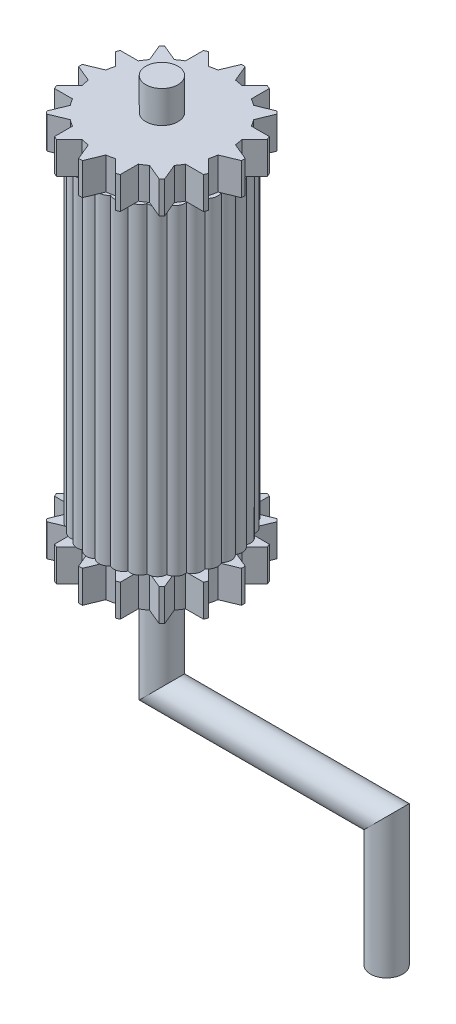
SolidWorks part; units mm, degrees
ref_plane "Front Plane" through (0, 0, 0) normal (1, 0, 0) x (0, 1, 0)
ref_plane "Top Plane" through (0, 0, 0) normal (0, 0, 1) x (0, 1, 0)
ref_plane "Right Plane" through (0, 0, 0) normal (0, 1, 0) x (-1, 0, 0)
sketch "Sketch2" plane through (0, 0, 0) normal (0, 1, 0) x (-1, 0, 0)
  arc A83 (20.6915, 2.1748) -> (20.6915, -2.1748) centre (18.625, 0) cw
  arc A84 (20.6915, -2.1748) -> (19.7872, -6.4292) centre (18.218, -3.8724) cw
  arc A85 (19.7872, -6.4292) -> (18.0181, -10.4027) centre (17.0148, -7.5755) cw
  arc A86 (18.0181, -10.4027) -> (15.4615, -13.9216) centre (15.0679, -10.9475) cw
  arc A87 (15.4615, -13.9216) -> (12.2291, -16.832) centre (12.4626, -13.8411) cw
  arc A88 (12.2291, -16.832) -> (8.4623, -19.0067) centre (9.3125, -16.1297) cw
  arc A89 (8.4623, -19.0067) -> (4.3257, -20.3508) centre (5.7554, -17.7134) cw
  arc A90 (4.3257, -20.3508) -> (0, -20.8055) centre (1.9468, -18.523) cw
  arc A91 (0, -20.8055) -> (-4.3257, -20.3508) centre (-1.9468, -18.523) cw
  arc A92 (-4.3257, -20.3508) -> (-8.4623, -19.0067) centre (-5.7554, -17.7134) cw
  arc A93 (-8.4623, -19.0067) -> (-12.2291, -16.832) centre (-9.3125, -16.1297) cw
  arc A94 (-12.2291, -16.832) -> (-15.4615, -13.9216) centre (-12.4626, -13.8411) cw
  arc A95 (-15.4615, -13.9216) -> (-18.0181, -10.4027) centre (-15.0679, -10.9475) cw
  arc A96 (-18.0181, -10.4027) -> (-19.7872, -6.4292) centre (-17.0148, -7.5755) cw
  arc A97 (-19.7872, -6.4292) -> (-20.6915, -2.1748) centre (-18.218, -3.8724) cw
  arc A98 (-20.6915, -2.1748) -> (-20.6915, 2.1748) centre (-18.625, 0) cw
  arc A99 (-20.6915, 2.1748) -> (-19.7872, 6.4292) centre (-18.218, 3.8724) cw
  arc A100 (-19.7872, 6.4292) -> (-18.0181, 10.4027) centre (-17.0148, 7.5755) cw
  arc A101 (-18.0181, 10.4027) -> (-15.4615, 13.9216) centre (-15.0679, 10.9475) cw
  arc A102 (-15.4615, 13.9216) -> (-12.2291, 16.832) centre (-12.4626, 13.8411) cw
  arc A103 (-12.2291, 16.832) -> (-8.4623, 19.0067) centre (-9.3125, 16.1297) cw
  arc A104 (-8.4623, 19.0067) -> (-4.3257, 20.3508) centre (-5.7554, 17.7134) cw
  arc A105 (-4.3257, 20.3508) -> (0, 20.8055) centre (-1.9468, 18.523) cw
  arc A106 (0, 20.8055) -> (4.3257, 20.3508) centre (1.9468, 18.523) cw
  arc A107 (4.3257, 20.3508) -> (8.4623, 19.0067) centre (5.7554, 17.7134) cw
  arc A108 (8.4623, 19.0067) -> (12.2291, 16.832) centre (9.3125, 16.1297) cw
  arc A109 (12.2291, 16.832) -> (15.4615, 13.9216) centre (12.4626, 13.8411) cw
  arc A110 (15.4615, 13.9216) -> (18.0181, 10.4027) centre (15.0679, 10.9475) cw
  arc A111 (18.0181, 10.4027) -> (19.7872, 6.4292) centre (17.0148, 7.5755) cw
  arc A112 (19.7872, 6.4292) -> (20.6915, 2.1748) centre (18.218, 3.8724) cw
  point P0 (0, 0)
  point P31 (0, 0)
  point P62 (0, 0)
  dimension "D1" = 3
extrude "Boss-Extrude2" add sketch "Sketch2" along normal blind 100
sketch "Sketch3" plane through (0, 0, 0) normal (0, -1, 0) x (1, 0, 0)
  line L0 (0, -57.0817) -> (0, 57.0817) construction
  line L1 (0, 25.375) -> (2.1167, 20.2647) construction
  line L2 (0, 25.375) -> (-2.1167, 20.2647) construction
  line L5 (-2.733, 20.1909) -> (2.733, 20.1909) construction
  line L32 (-2.733, 20.1909) -> (-0.5885, 25.3682)
  line L33 (2.733, 20.1909) -> (0.5885, 25.3682)
  line L34 (5.2017, 19.6998) -> (9.1643, 23.6623)
  line L35 (10.2517, 17.6081) -> (10.2517, 23.2119)
  line L36 (12.3446, 16.2096) -> (17.5219, 18.3541)
  line L37 (16.2096, 12.3446) -> (18.3541, 17.5219)
  line L38 (17.6081, 10.2517) -> (23.2119, 10.2517)
  line L39 (19.6998, 5.2017) -> (23.6623, 9.1643)
  line L40 (20.1909, 2.733) -> (25.3682, 0.5885)
  line L41 (20.1909, -2.733) -> (25.3682, -0.5885)
  line L42 (19.6998, -5.2017) -> (23.6623, -9.1643)
  line L43 (17.6081, -10.2517) -> (23.2119, -10.2517)
  line L44 (16.2096, -12.3446) -> (18.3541, -17.5219)
  line L45 (12.3446, -16.2096) -> (17.5219, -18.3541)
  line L46 (10.2517, -17.6081) -> (10.2517, -23.2119)
  line L47 (5.2017, -19.6998) -> (9.1643, -23.6623)
  line L48 (2.733, -20.1909) -> (0.5885, -25.3682)
  line L49 (-2.733, -20.1909) -> (-0.5885, -25.3682)
  line L50 (-5.2017, -19.6998) -> (-9.1643, -23.6623)
  line L51 (-10.2517, -17.6081) -> (-10.2517, -23.2119)
  line L52 (-12.3446, -16.2096) -> (-17.5219, -18.3541)
  line L53 (-16.2096, -12.3446) -> (-18.3541, -17.5219)
  line L54 (-17.6081, -10.2517) -> (-23.2119, -10.2517)
  line L55 (-19.6998, -5.2017) -> (-23.6623, -9.1643)
  line L56 (-20.1909, -2.733) -> (-25.3682, -0.5885)
  line L57 (-20.1909, 2.733) -> (-25.3682, 0.5885)
  line L58 (-19.6998, 5.2017) -> (-23.6623, 9.1643)
  line L59 (-17.6081, 10.2517) -> (-23.2119, 10.2517)
  line L60 (-16.2096, 12.3446) -> (-18.3541, 17.5219)
  line L61 (-12.3446, 16.2096) -> (-17.5219, 18.3541)
  line L62 (-10.2517, 17.6081) -> (-10.2517, 23.2119)
  line L63 (-5.2017, 19.6998) -> (-9.1643, 23.6623)
  arc A28 (-16.2096, 12.3446) -> (-17.6081, 10.2517) centre (0, 0) ccw
  arc A29 (-23.2119, 10.2517) -> (-23.6623, 9.1643) centre (0, 0) ccw
  arc A30 (-17.5219, 18.3541) -> (-18.3541, 17.5219) centre (0, 0) ccw
  arc A31 (-10.2517, 17.6081) -> (-12.3446, 16.2096) centre (0, 0) ccw
  arc A32 (-9.1643, 23.6623) -> (-10.2517, 23.2119) centre (0, 0) ccw
  arc A33 (0.5885, 25.3682) -> (-0.5885, 25.3682) centre (0, 0) ccw
  arc A34 (10.2517, 23.2119) -> (9.1643, 23.6623) centre (0, 0) ccw
  arc A35 (-2.733, 20.1909) -> (-5.2017, 19.6998) centre (0, 0) ccw
  arc A36 (5.2017, 19.6998) -> (2.733, 20.1909) centre (0, 0) ccw
  arc A37 (18.3541, 17.5219) -> (17.5219, 18.3541) centre (0, 0) ccw
  arc A38 (12.3446, 16.2096) -> (10.2517, 17.6081) centre (0, 0) ccw
  arc A39 (17.6081, 10.2517) -> (16.2096, 12.3446) centre (0, 0) ccw
  arc A40 (23.6623, 9.1643) -> (23.2119, 10.2517) centre (0, 0) ccw
  arc A41 (25.3682, -0.5885) -> (25.3682, 0.5885) centre (0, 0) ccw
  arc A42 (23.2119, -10.2517) -> (23.6623, -9.1643) centre (0, 0) ccw
  arc A43 (20.1909, 2.733) -> (19.6998, 5.2017) centre (0, 0) ccw
  arc A44 (19.6998, -5.2017) -> (20.1909, -2.733) centre (0, 0) ccw
  arc A45 (17.5219, -18.3541) -> (18.3541, -17.5219) centre (0, 0) ccw
  arc A46 (9.1643, -23.6623) -> (10.2517, -23.2119) centre (0, 0) ccw
  arc A47 (10.2517, -17.6081) -> (12.3446, -16.2096) centre (0, 0) ccw
  arc A48 (16.2096, -12.3446) -> (17.6081, -10.2517) centre (0, 0) ccw
  arc A49 (-0.5885, -25.3682) -> (0.5885, -25.3682) centre (0, 0) ccw
  arc A50 (-10.2517, -23.2119) -> (-9.1643, -23.6623) centre (0, 0) ccw
  arc A51 (-5.2017, -19.6998) -> (-2.733, -20.1909) centre (0, 0) ccw
  arc A52 (2.733, -20.1909) -> (5.2017, -19.6998) centre (0, 0) ccw
  arc A53 (-18.3541, -17.5219) -> (-17.5219, -18.3541) centre (0, 0) ccw
  arc A54 (-23.6623, -9.1643) -> (-23.2119, -10.2517) centre (0, 0) ccw
  arc A55 (-12.3446, -16.2096) -> (-10.2517, -17.6081) centre (0, 0) ccw
  arc A56 (-17.6081, -10.2517) -> (-16.2096, -12.3446) centre (0, 0) ccw
  arc A57 (-20.1909, -2.733) -> (-19.6998, -5.2017) centre (0, 0) ccw
  arc A58 (-25.3682, 0.5885) -> (-25.3682, -0.5885) centre (0, 0) ccw
  arc A59 (-19.6998, 5.2017) -> (-20.1909, 2.733) centre (0, 0) ccw
  point P13 (0, 57.0817)
  point P17 (0, 47.4976)
  point P78 (0, 0)
  dimension "D2" = 50.75
  dimension "D1" = 40.75
  dimension "D3" = 22.5
  dimension "D4" = 22.5
  dimension "D5" = 5.466
  dimension "D6" = 16
extrude "Boss-Extrude3" add sketch "Sketch3" along normal blind 10
ref_plane "Plane1" through (0, 50, 0) normal (0, 1, 0) x (1, 0, 0)
mirror "Mirror1" about plane through (0, 50, 0) normal (0, 1, 0) of "Boss-Extrude3"
sketch "Sketch4" plane through (0, -10, 0) normal (0, -1, 0) x (1, 0, 0)
  circle A0 centre (0, 0) radius 5
  dimension "D1" = 10
extrude "Boss-Extrude4" add sketch "Sketch4" along normal blind 10
mirror "Mirror2" about plane through (0, 50, 0) normal (0, 1, 0) of "Boss-Extrude4"
sketch "Sketch6" plane through (0, 0, 0) normal (0, 0, 1) x (0, 1, 0)
  line L0 (-20, 0) -> (-45, 0)
  line L1 (-20, 5) -> (-20, -5) construction
  line L2 (-45, 0) -> (-45, -70)
  line L3 (-45, -70) -> (-85, -70)
  dimension "D1" = 25
  dimension "D2" = 70
  dimension "D3" = 40
sweep "Sweep1" add path "Sketch6" circular profile diameter 10 parameters "D3"=10
